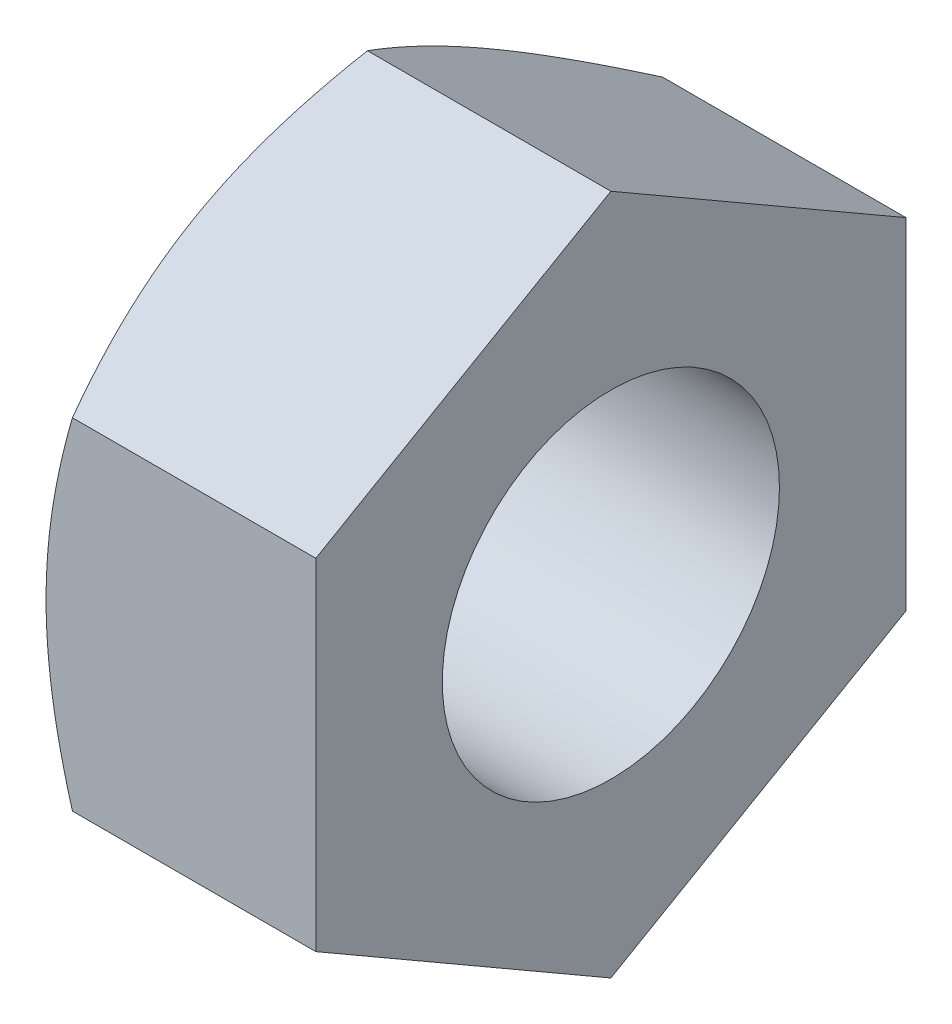
SolidWorks part; units mm, degrees
material "Chrome Stainless Steel"
ref_plane "Front Plane" through (0, 0, 0) normal (0, 0, 1) x (1, 0, 0)
ref_plane "Top Plane" through (0, 0, 0) normal (0, 1, 0) x (1, 0, 0)
ref_plane "Right Plane" through (0, 0, 0) normal (1, 0, 0) x (0, 0, -1)
sketch "Sketch1" plane through (0, 0, 0) normal (1, 0, 0) x (0, 0, -1)
  line L1 (0, 4.0415) -> (-3.5, 2.0207)
  line L2 (-3.5, 2.0207) -> (-3.5, -2.0207)
  line L3 (-3.5, -2.0207) -> (0, -4.0415)
  line L4 (0, -4.0415) -> (3.5, -2.0207)
  line L5 (3.5, -2.0207) -> (3.5, 2.0207)
  line L6 (3.5, 2.0207) -> (0, 4.0415)
  circle A0 centre (0, 0) radius 3.5 construction
extrude "Boss-Extrude1" add sketch "Sketch1" against normal blind 3.2
sketch "Sketch2" plane through (0, 0, 0) normal (0, 0, 1) x (1, 0, 0)
  line L0 (-2.2385, 0) -> (0.6157, 0) construction
  line L1 (-3.2, 3.5) -> (-2.8874, 4.0415)
  line L2 (-3.2, 4.0415) -> (-3.2, 2.0207) construction
  line L3 (-3.2, 4.0415) -> (0, 4.0415) construction
  line L4 (-2.8874, 4.0415) -> (-3.2, 4.0415)
  line L5 (-3.2, 4.0415) -> (-3.2, 3.5)
revolve "Cut-Revolve1" cut sketch "Sketch2" about L0
sketch "Sketch5" plane through (0, 0, 0) normal (0, 0, 1) x (1, 0, 0)
  line L0 (0, 0) -> (-3.2, 0) construction
  line L1 (-2.8874, 4.0415) -> (0, 4.0415) construction
  line L2 (-3.2, 0) -> (-1.8, 0)
  line L3 (-3.2, 0) -> (-3.2, 4.0415)
  line L4 (-3.2, 4.0415) -> (-1.8, 4.0415)
  line L5 (-1.8, 0) -> (-1.8, 4.0415)
  dimension "T1" = 1.8
revolve "Cut-Revolve2" [suppressed] cut sketch "Sketch5" about L0
sketch "Sketch6" plane through (0, 0, 0) normal (0, 0, 1) x (1, 0, 0)
  line L0 (-1.8, 3.5) -> (-1.4874, 4.0415)
  line L1 (-1.8, 0) -> (-1.8, 4.0415) construction
  line L2 (-3.2, 4.0415) -> (-1.8, 4.0415) construction
  line L3 (-1.4874, 4.0415) -> (-1.8, 4.0415)
  line L4 (-1.8, 4.0415) -> (-1.8, 3.5)
  line L5 (0, 3.5) -> (-0.3126, 4.0415)
  line L6 (0, 4.0415) -> (0, 2.0207) construction
  line L7 (-0.3126, 4.0415) -> (0, 4.0415)
  line L8 (0, 4.0415) -> (0, 3.5)
  line L9 (-1.687, 0) -> (0.4573, 0) construction
revolve "Cut-Revolve3" [suppressed] cut sketch "Sketch6" about L9
sketch "Sketch7" plane through (0, 0, 0) normal (1, 0, 0) x (0, 0, -1)
  circle A0 centre (0, 0) radius 2
  dimension "D1" = 4
extrude "Cut-Extrude1" cut sketch "Sketch7" against normal through all
equation "\"Factor\"= 1.082532"
equation "\"M\"=4.000000"
equation "\"Pitch\"=0.7"
equation "\"STD\"= round ( \"M\" - \"Factor\" * \"Pitch\" , 3 )"
